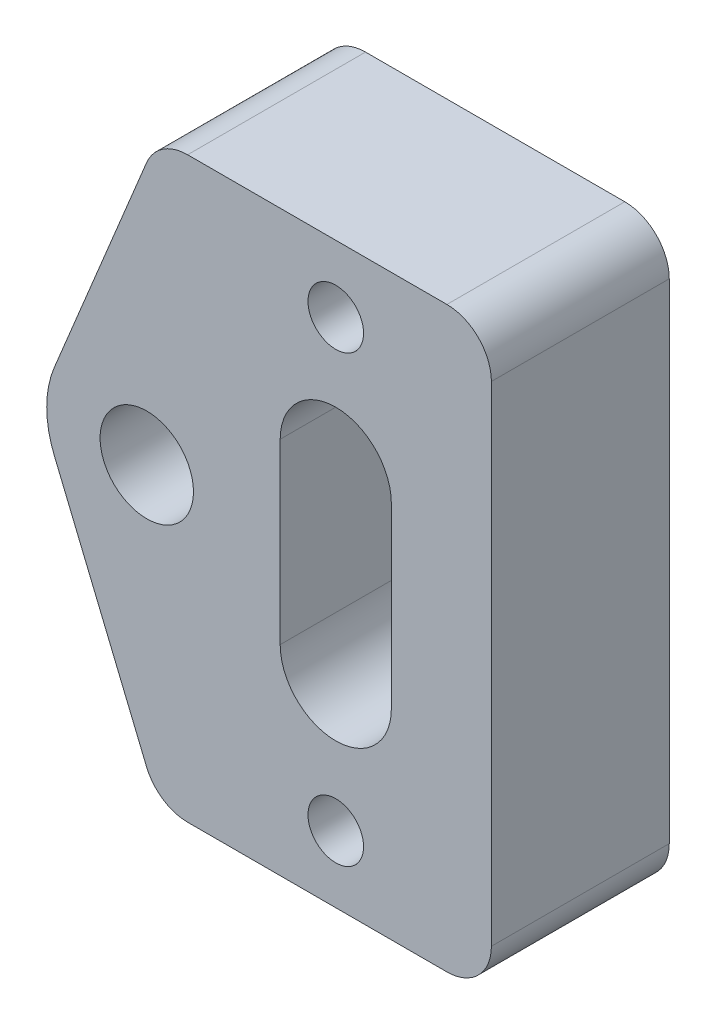
SolidWorks part; units mm, degrees
material "6061 合金"
ref_plane "前视基准面" through (0, 0, 0) normal (0, 0, 1) x (1, 0, 0)
ref_plane "上视基准面" through (0, 0, 0) normal (0, 1, 0) x (1, 0, 0)
ref_plane "右视基准面" through (0, 0, 0) normal (1, 0, 0) x (0, 0, -1)
sketch "草图1" plane through (0, 0, 0) normal (0, 0, 1) x (1, 0, 0)
  line L0 (0, 0) -> (8, 0) construction
  line L1 (0.5, -13) -> (15.5, -13)
  line L3 (0.5, 13) -> (15.5, 13)
  line L4 (15.5, -13) -> (15.5, 13)
  line L5 (0.5, -13) -> (15.5, 13) construction
  line L6 (0.5, 13) -> (15.5, -13) construction
  line L8 (-4.1593, -1.7177) -> (0.5, -13)
  line L9 (-4.1593, 1.7177) -> (0.5, 13)
  circle A0 centre (0, 0) radius 1.5
  arc A1 (-4.1593, 1.7177) -> (-4.1593, -1.7177) centre (0, 0) ccw
  point P4 (8, 0)
  dimension "D1" = 3
  dimension "D2" = 9
  dimension "D3" = 8
  dimension "D4" = 26
  dimension "D5" = 15
  dimension "D6" = 135.122
extrude "凸台-拉伸1" add sketch "草图1" along normal blind 8
sketch "草图2" plane through (0, 0, 8) normal (0, 0, 1) x (1, 0, 0)
  line L0 (0, 0) -> (8.5, 0) construction
  line L1 (8.5, 10) -> (8.5, -10) construction
  line L2 (15.5, -13) -> (15.5, 13) construction
  circle A0 centre (8.5, 10) radius 1
  circle A1 centre (8.5, -10) radius 1
  dimension "D2" = 2
  dimension "D1" = 20
  dimension "D3" = 7
extrude "切除-拉伸1" cut sketch "草图2" against normal blind 33
fillet "圆角1" radius 2 4 edges at (0.5, 13, 4) (15.5, 13, 4) (0.5, -13, 4) (15.5, -13, 4)
hole_wizard "M3 螺纹孔1" positions "草图3" profile "草图4" tap size "M3" standard "GB" end condition through all
sketch "草图3" plane through (0, 0, 8) normal (0, 0, 1) x (1, 0, 0)
  point P0 (8.5, 10)
  point P3 (8.5, -10)
sketch "草图4" plane through (8.5, 10, 8) normal (1, 0, 0) x (0, -1, 0)
  line L0 (0, 0) -> (0, 8)
  line L1 (0, 8) -> (1.25, 8)
  line L2 (1.25, 8) -> (1.25, 0)
  line L5 (1.25, 0) -> (0, 0)
  line L11 (0, -6.35) -> (0, 107.95) construction
  dimension "通孔螺纹孔钻头直径" = 2.5
  dimension "通孔螺纹孔钻头深度" = 8
cosmetic thread "孔螺蚊线1" parameters "D2"=3
cosmetic thread "孔螺蚊线2" parameters "D2"=3
sketch "草图8" plane through (0, 0, 0) normal (0, 0, -1) x (-1, 0, 0)
  circle A0 centre (0, 0) radius 4.5
  arc A1 (4.1593, -1.7177) -> (4.1593, 1.7177) centre (0, 0) ccw construction
  circle A2 centre (0, 0) radius 1.5 construction
  circle A3 centre (0, 0) radius 1.5
extrude "凸台-拉伸2" add sketch "草图8" along normal blind 2.3
hole_wizard "M5 螺纹孔1" positions "草图10" profile "草图11" tap size "M5" standard "GB"
sketch "草图10" plane through (0, 0, 8) normal (0, 0, 1) x (1, 0, 0)
  point P0 (0, 0)
sketch "草图11" plane through (0, 0, 8) normal (1, 0, 0) x (0, -1, 0)
  line L0 (0, 0) -> (0, 21.2618)
  line L1 (0, 21.2618) -> (2.1, 20)
  line L2 (2.1, 20) -> (2.1, 0)
  line L5 (2.1, 0) -> (0, 0)
  line L10 (0, 21.2618) -> (-2.1, 20) construction
  line L11 (0, -6.35) -> (0, 107.95) construction
  dimension "螺纹孔钻头直径" = 4.2
  dimension "螺纹孔钻头深度" = 20
  dimension "导头角度" = 118
cosmetic thread "孔螺蚊线3" parameters "D1"=10, "D2"=5
sketch "草图12" plane through (0, 0, 0) normal (0, 0, -1) x (-1, 0, 0)
  line L0 (-8.5, 10) -> (-8.5, -10) construction
  line L1 (-8.5, 4) -> (-8.5, -4) construction
  line L2 (-6, 4) -> (-6, -4)
  line L3 (-11, 4) -> (-11, -4)
  arc A0 (-6, 4) -> (-11, 4) centre (-8.5, 4) ccw
  arc A1 (-11, -4) -> (-6, -4) centre (-8.5, -4) ccw
  point P6 (-8.5, 0)
  dimension "D1" = 2.5
  dimension "D2" = 8
extrude "切除-拉伸2" cut sketch "草图12" against normal blind 20
